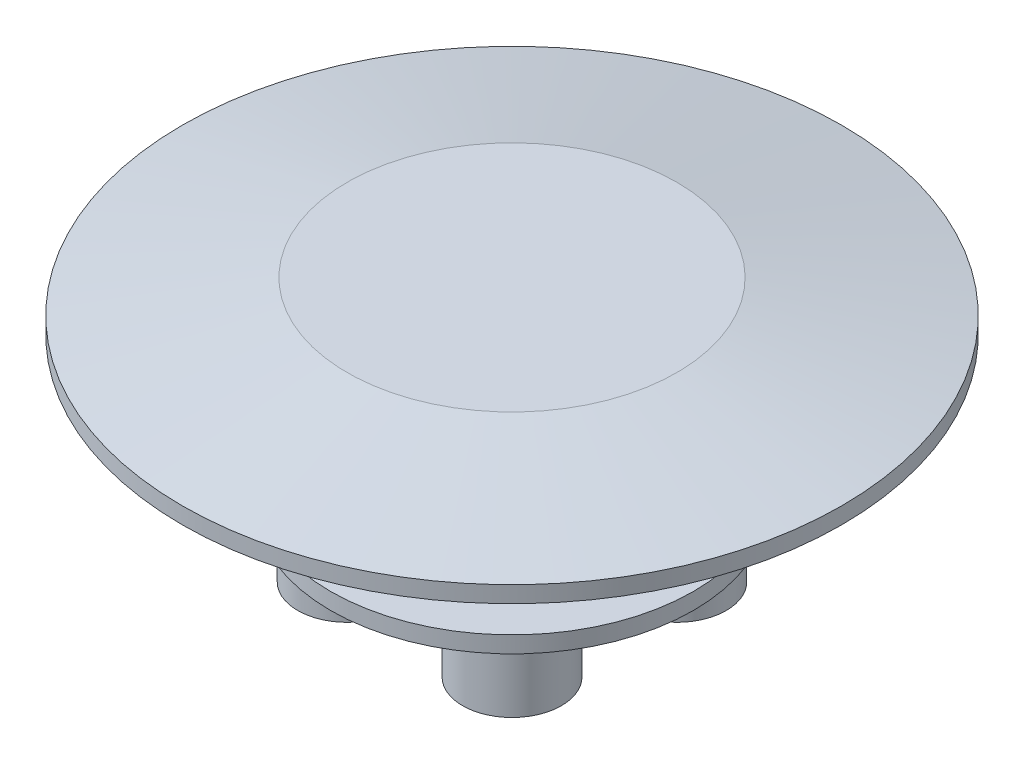
SolidWorks part; units mm, degrees
ref_plane "Front Plane" through (0, 0, 0) normal (0, 0, 1) x (1, 0, 0)
ref_plane "Top Plane" through (0, 0, 0) normal (0, 1, 0) x (1, 0, 0)
ref_plane "Right Plane" through (0, 0, 0) normal (1, 0, 0) x (0, 0, -1)
sketch "Sketch1" plane through (0, 0, 0) normal (0, 1, 0) x (1, 0, 0)
  circle A0 centre (0, 0) radius 100
  dimension "D1" = 200
extrude "Boss-Extrude1" add sketch "Sketch1" along normal blind 5
ref_plane "Plane1" through (0, 15, 0) normal (0, -1, 0) x (-1, 0, 0)
sketch "Sketch2" plane through (0, 15, 0) normal (0, -1, 0) x (-1, 0, 0)
  circle A0 centre (0, 0) radius 50
  dimension "D1" = 100
extrude "Boss-Extrude2" add sketch "Sketch2" along normal blind 5 separate body
sketch "Sketch3" plane through (0, 5, 0) normal (0, 1, 0) x (1, 0, 0)
  circle A0 centre (0, 0) radius 10
  circle A1 centre (0, 0) radius 5
  dimension "D1" = 20
  dimension "D2" = 10
extrude "Boss-Extrude3" add sketch "Sketch3" along normal up to surface (5 mm away) up to face at (0, 10, -50)
sketch "Sketch4" plane through (0, 0, 0) normal (0, 0, 1) x (1, 0, 0)
  line L0 (50, 15) -> (100, 5)
  line L2 (100, 5) -> (-100, 5) construction
  line L4 (50, 10) -> (50, 15)
  line L5 (50, 10) -> (0, 10)
  line L6 (-10, 10) -> (10, 10) construction
  line L7 (0, 10) -> (0, 5)
  line L9 (0, 5) -> (100, 5)
ref_axis "Axis1" through (0, 54.0722, 0) along (0, -1, 0)
revolve "Revolve1" add sketch "Sketch4" angle 360 about axis through (0, 54.0722, 0) along (0, -1, 0)
sketch "Sketch5" plane through (0, 0, 0) normal (0, -1, 0) x (1, 0, 0)
  circle A0 centre (0, 0) radius 22.5
  dimension "D1" = 45
extrude "Boss-Extrude4" add sketch "Sketch5" along normal blind 40
sketch "Sketch6" plane through (0, -40, 0) normal (0, -1, 0) x (1, 0, 0)
  circle A0 centre (0, 0) radius 55
  dimension "D1" = 110
extrude "Boss-Extrude5" add sketch "Sketch6" along normal blind 5
sketch "Sketch7" plane through (0, -45, 0) normal (0, -1, 0) x (1, 0, 0)
  circle A0 centre (-25, -25) radius 15
  circle A1 centre (25, -25) radius 15
  circle A2 centre (25, 25) radius 15
  circle A3 centre (-25, 25) radius 15
  dimension "D4" = 30
  dimension "D3" = 50
extrude "Boss-Extrude6" add sketch "Sketch7" along normal blind 20
sketch "Sketch9" plane through (0, -45, 0) normal (0, -1, 0) x (1, 0, 0)
  circle A1 centre (0, 40) radius 2.5
  circle A2 centre (40, 0) radius 2.5
  circle A3 centre (0, -40) radius 2.5
  circle A4 centre (-40, 0) radius 2.5
  point P11 (0, 0)
  dimension "D1" = 4
  dimension "D2" = 5
extrude "Cut-Extrude2" cut sketch "Sketch9" against normal up to surface (5 mm away) up to face at (0, -40, -22.5)
sketch "Sketch11" plane through (0, -40, 0) normal (0, 1, 0) x (1, 0, 0)
  circle A0 centre (0, 40) radius 10
  circle A1 centre (0, 40) radius 2.5 construction
  circle A2 centre (40, 0) radius 10
  circle A3 centre (0, -40) radius 10
  circle A4 centre (-40, 0) radius 10
  point P13 (0, 0)
  dimension "D1" = 20
  dimension "D2" = 4
extrude "Cut-Extrude3" cut sketch "Sketch11" against normal blind 1
